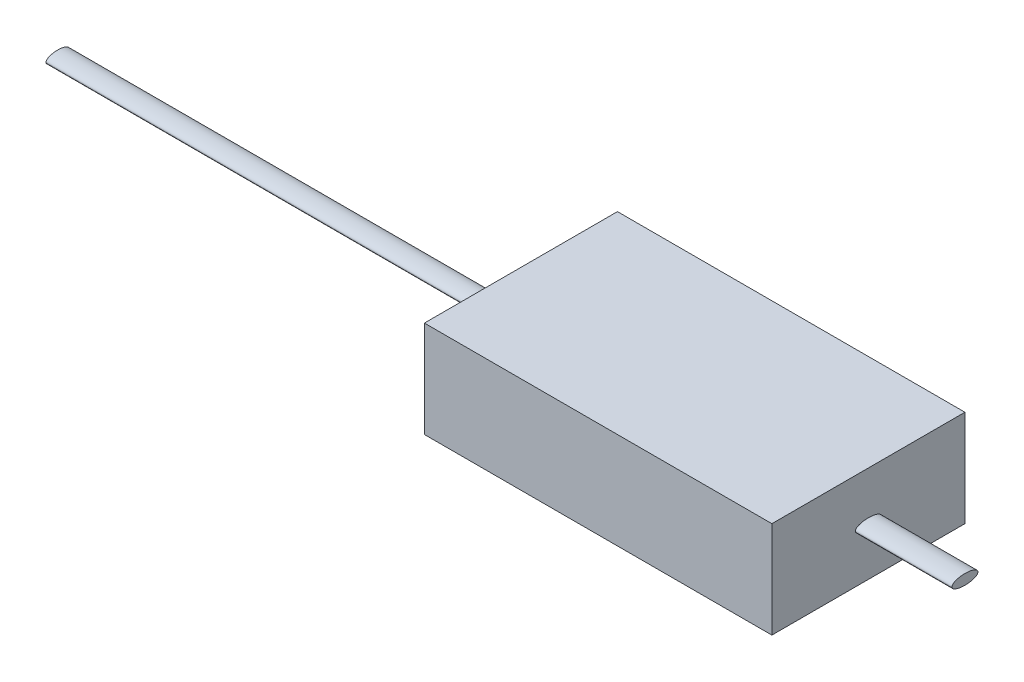
SolidWorks part; units mm, degrees
ref_plane "Front Plane" through (0, 0, 0) normal (0, 0, 1) x (1, 0, 0)
ref_plane "Top Plane" through (0, 0, 0) normal (0, 1, 0) x (1, 0, 0)
ref_plane "Right Plane" through (0, 0, 0) normal (1, 0, 0) x (0, 0, -1)
sketch "Sketch1" plane through (0, 0, 0) normal (0, 1, 0) x (1, 0, 0)
  line L1 (-87.8056, 3.087) -> (2.1944, 3.087)
  line L2 (-87.8056, 3.087) -> (-87.8056, -46.913)
  line L3 (-87.8056, -46.913) -> (2.1944, -46.913)
  line L4 (2.1944, 3.087) -> (2.1944, -46.913)
  line L5 (-87.8056, 3.087) -> (2.1944, -46.913) construction
  line L6 (-87.8056, -46.913) -> (2.1944, 3.087) construction
  point P4 (-42.8056, -21.913)
  dimension "D1" = 90
  dimension "D2" = 50
extrude "Boss-Extrude1" add sketch "Sketch1" along normal blind 25
sketch "Sketch2" plane through (-87.8056, 0, 0) normal (-1, 0, 0) x (0, 0, 1)
  ellipse E0 centre (21.913, 12.5) end of major axis (24.926, 12.5) minor radius 1.2469
extrude "Boss-Extrude2" add sketch "Sketch2" along normal blind 120
sketch "Sketch3" plane through (2.1944, 0, 0) normal (1, 0, 0) x (0, 0, -1)
  ellipse E0 centre (-21.913, 12.5) end of major axis (-18.526, 12.5) minor radius 1.3278
extrude "Boss-Extrude3" add sketch "Sketch3" along normal blind 25
